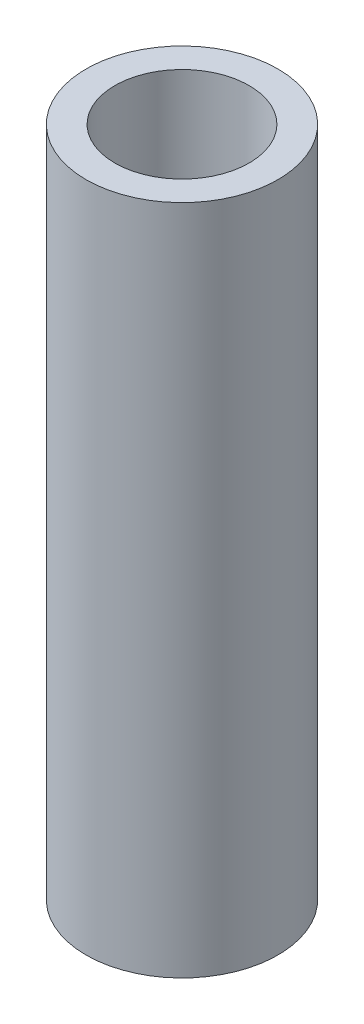
SolidWorks part; units mm, degrees
ref_plane "Front Plane" through (0, 0, 0) normal (0, 0, 1) x (1, 0, 0)
ref_plane "Top Plane" through (0, 0, 0) normal (0, 1, 0) x (1, 0, 0)
ref_plane "Right Plane" through (0, 0, 0) normal (1, 0, 0) x (0, 0, -1)
sketch "Feed Tube Sketch" plane through (0, 0, 0) normal (0, 1, 0) x (1, 0, 0)
  circle A0 centre (0, 0) radius 10
  circle A1 centre (0, 0) radius 7
  dimension "D1" = 20
  dimension "D2" = 14
extrude "Feed Tube" add sketch "Feed Tube Sketch" along normal blind 70
